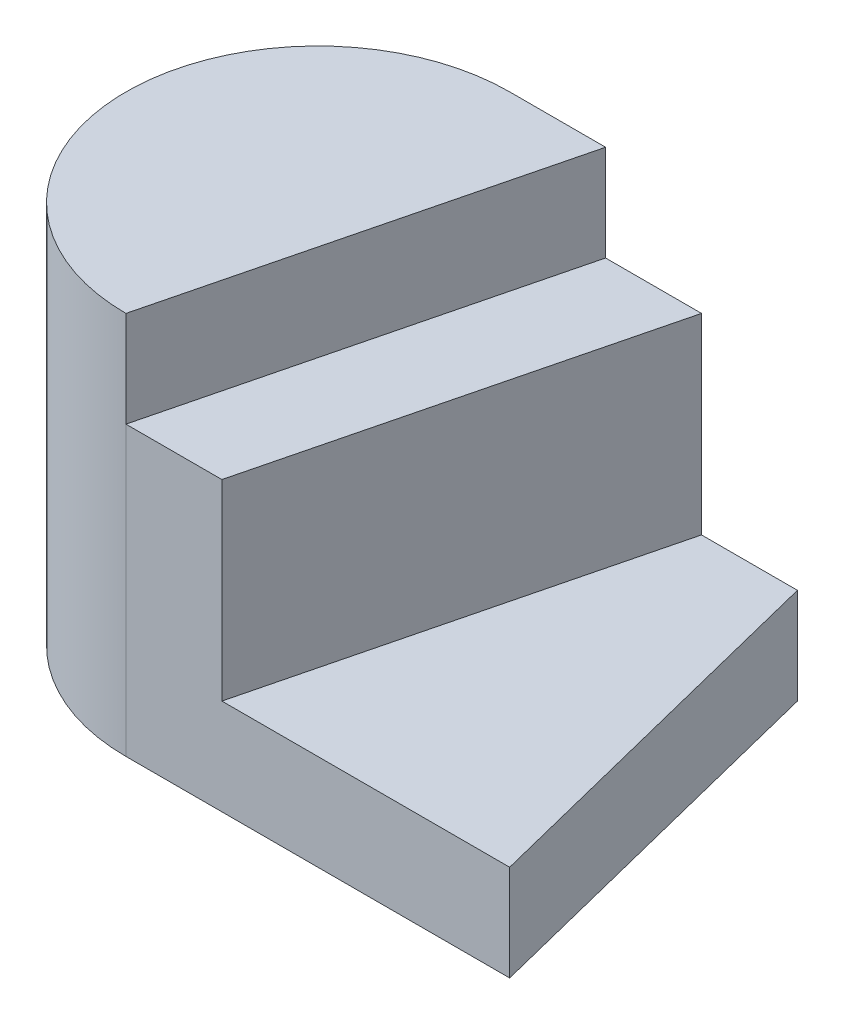
SolidWorks part; units mm, degrees
ref_plane "前基準面" through (0, 0, 0) normal (0, 0, 1) x (1, 0, 0)
ref_plane "上基準面" through (0, 0, 0) normal (0, 1, 0) x (1, 0, 0)
ref_plane "右基準面" through (0, 0, 0) normal (1, 0, 0) x (0, 0, -1)
sketch "草圖1" plane through (0, 0, 0) normal (0, 1, 0) x (1, 0, 0)
  line L0 (0, 10) -> (15, 10)
  line L1 (15, 10) -> (20, -10)
  line L2 (20, -10) -> (0, -10)
  arc A0 (0, 10) -> (0, -10) centre (0, 0) ccw
  dimension "D1" = 20
  dimension "D2" = 15
  dimension "D3" = 20
extrude "填料-伸長1" add sketch "草圖1" along normal blind 20
sketch "草圖2" plane through (0, 20, 0) normal (0, 1, 0) x (1, 0, 0)
  line L0 (5, 10) -> (0, -10)
  line L1 (15, 10) -> (0, 10) construction
  line L2 (0, -10) -> (20, -10) construction
  line L3 (5, 10) -> (10, 10)
  line L4 (10, 10) -> (5, -10)
  line L5 (0, -10) -> (5, -10)
  dimension "D1" = 5
  dimension "D2" = 5
  dimension "D3" = 15
extrude "除料-伸長1" cut sketch "草圖2" against normal blind 5
sketch "草圖3" plane through (0, 15, 0) normal (0, 1, 0) x (1, 0, 0)
  line L4 (10, 10) -> (5, -10)
  line L5 (5, -10) -> (20, -10)
  line L6 (20, -10) -> (15, 10)
  line L7 (15, 10) -> (10, 10)
  line L8 (10, 10) -> (5, -10)
  line L9 (5, -10) -> (20, -10)
  line L10 (20, -10) -> (15, 10)
  line L11 (15, 10) -> (10, 10)
  dimension "D1" = 0
extrude "除料-伸長2" cut sketch "草圖3" against normal blind 10 and the other way through all
